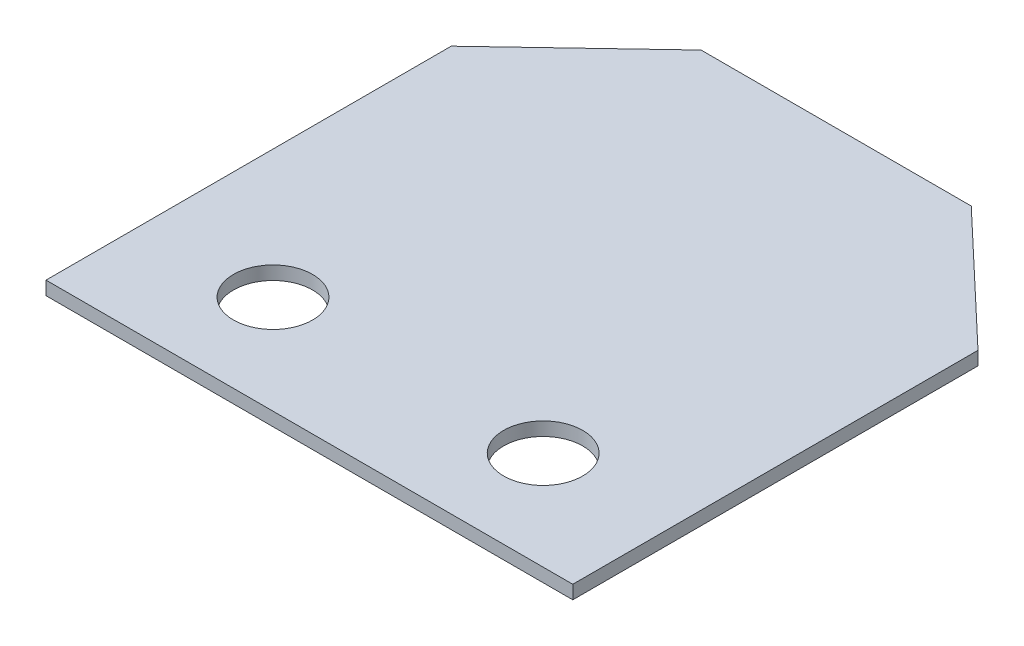
SolidWorks part; units mm, degrees
ref_plane "Plano frontal" through (0, 0, 0) normal (0, 0, 1) x (1, 0, 0)
ref_plane "Plano superior" through (0, 0, 0) normal (0, 1, 0) x (1, 0, 0)
ref_plane "Plano direito" through (0, 0, 0) normal (1, 0, 0) x (0, 0, -1)
sketch "Esboço1" plane through (0, 0, 0) normal (0, 1, 0) x (1, 0, 0)
  line L0 (-20, 48) -> (-39, 30)
  line L1 (-39, -30) -> (39, -30)
  line L2 (-39, -30) -> (-39, 30)
  line L4 (39, -30) -> (39, 30)
  line L5 (-39, -30) -> (39, 30) construction
  line L6 (-39, 30) -> (39, -30) construction
  line L9 (-20, 48) -> (20, 48)
  line L11 (20, 48) -> (39, 30)
  line L12 (0, 55.5968) -> (0, -62.9596) construction
  circle A0 centre (-20, -15.3846) radius 5.857
  circle A1 centre (20, -15.3846) radius 5.857
  point P0 (0, 0)
  point P12 (-20, -19.7637)
  point P13 (0, 0)
  point P14 (-20, -15.3846)
  dimension "D1" = 78
  dimension "D2" = 60
  dimension "D3" = 40
  dimension "D4" = 18
extrude "Ressalto-extrusão1" add sketch "Esboço1" along normal blind 2
